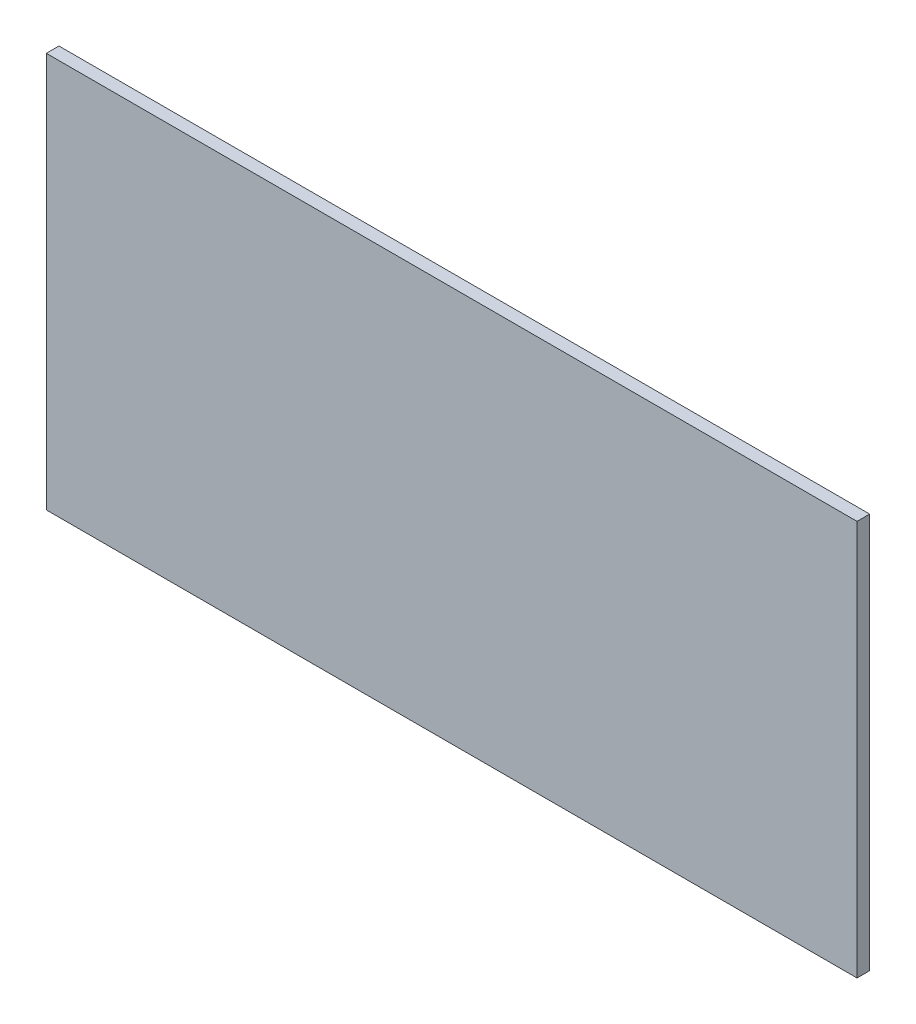
SolidWorks part; units mm, degrees
material "Pine"
ref_plane "Front Plane" through (0, 0, 0) normal (0, 0, 1) x (1, 0, 0)
ref_plane "Top Plane" through (0, 0, 0) normal (0, 1, 0) x (1, 0, 0)
ref_plane "Right Plane" through (0, 0, 0) normal (1, 0, 0) x (0, 0, -1)
sketch "Sketch1" plane through (0, 0, 0) normal (0, 0, 1) x (1, 0, 0)
  line L1 (585.7875, 0) -> (-585.7875, 0)
  line L2 (585.7875, 0) -> (585.7875, 571.5)
  line L3 (585.7875, 571.5) -> (-585.7875, 571.5)
  line L4 (-585.7875, 0) -> (-585.7875, 571.5)
  point P7 (0, 0)
  dimension "D1" = 1171.575
  dimension "D2" = 571.5
extrude "Boss-Extrude1" add sketch "Sketch1" along normal blind 18.2562
